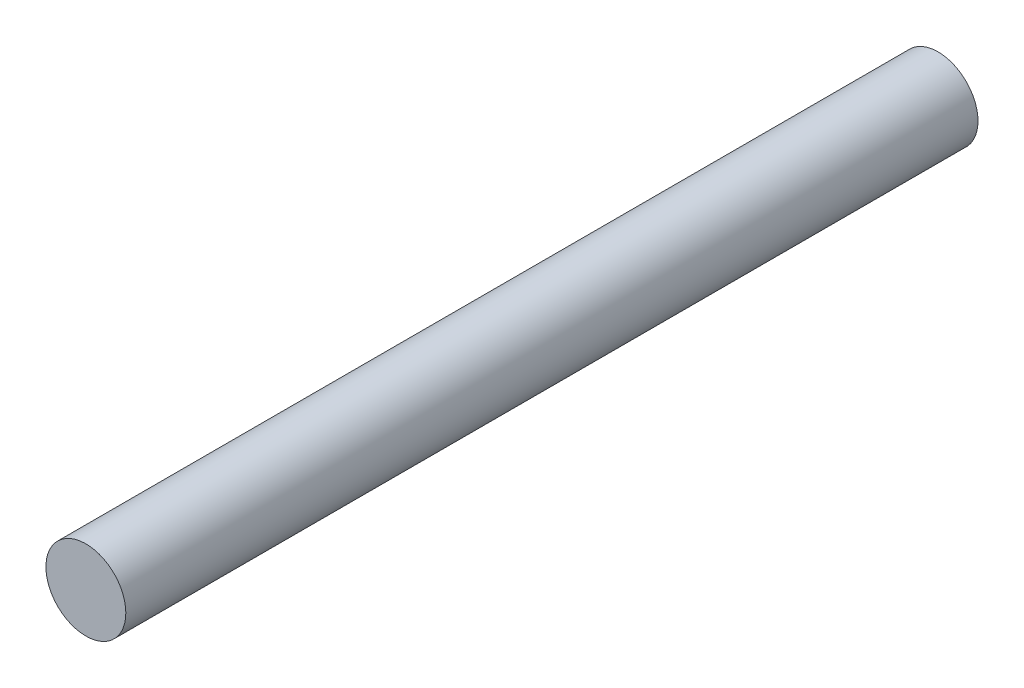
SolidWorks part; units mm, degrees
ref_plane "Plan de face" through (0, 0, 0) normal (0, 0, 1) x (1, 0, 0)
ref_plane "Plan de dessus" through (0, 0, 0) normal (0, 1, 0) x (1, 0, 0)
ref_plane "Plan de droite" through (0, 0, 0) normal (1, 0, 0) x (0, 0, -1)
sketch "Esquisse1" plane through (0, 0, 0) normal (0, 0, 1) x (1, 0, 0)
  circle A0 centre (0, 0) radius 1.5
  dimension "D1" = 3
extrude "Extrusion1" add sketch "Esquisse1" along normal blind 32
